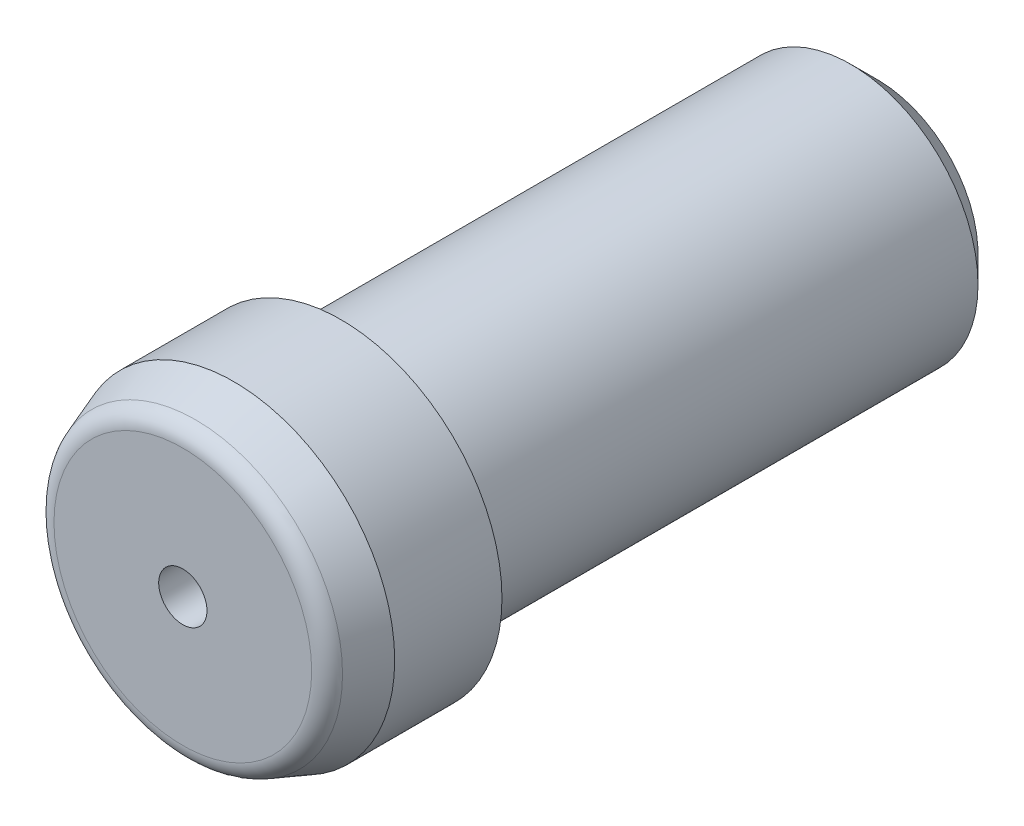
SolidWorks part; units mm, degrees
ref_plane "Front" through (0, 0, 0) normal (0, 0, 1) x (1, 0, 0)
ref_plane "Top" through (0, 0, 0) normal (0, 1, 0) x (1, 0, 0)
ref_plane "Right" through (0, 0, 0) normal (1, 0, 0) x (0, 0, -1)
sketch "Sketch1" plane through (0, 0, 0) normal (1, 0, 0) x (0, 0, -1)
  line L0 (0, 0) -> (0, 6.7417)
  line L1 (0, 6.7417) -> (2.413, 7.62)
  line L2 (2.413, 7.62) -> (7.493, 7.62)
  line L3 (7.493, 7.62) -> (7.493, 6.0325)
  line L4 (7.493, 6.0325) -> (32.893, 6.0325)
  line L5 (32.893, 6.0325) -> (32.893, 0)
  line L6 (32.893, 0) -> (0, 0)
  line L7 (0, 0) -> (-15.9922, 0) construction
  line L8 (0, 0) -> (0, -14.393) construction
  dimension "A" = 15.24
  dimension "D1" = 20
  dimension "D3" = 5.08
  dimension "D2" = 2.413
  dimension "D4" = 25.4
ref_axis "Axis1" through (0, 0, -133.35) along (0, 0, 1)
revolve "Revolve1" add sketch "Sketch1" angle 360 about axis through (0, 0, -133.35) along (0, 0, 1)
sketch "Sketch2" plane through (0, 0, 0) normal (1, 0, 0) x (0, 0, -1)
  line L0 (7.493, 7.62) -> (7.493, 6.0325) construction
  line L1 (7.239, 5.7785) -> (8.255, 5.7785) construction
  line L2 (7.239, 5.7785) -> (7.239, 6.7945) construction
  line L3 (7.239, 6.7945) -> (8.255, 6.7945) construction
  line L4 (8.255, 5.7785) -> (8.255, 6.7945) construction
  line L5 (7.493, 6.0325) -> (32.893, 6.0325) construction
  line L6 (7.2948, 6.3423) -> (7.747, 6.7945)
  line L7 (7.8028, 5.8343) -> (8.255, 6.2865)
  line L8 (7.239, 6.2076) -> (7.239, 5.969)
  line L9 (7.4295, 5.7785) -> (7.6681, 5.7785)
  line L10 (8.255, 6.2865) -> (8.255, 6.7945)
  line L11 (8.255, 6.7945) -> (7.747, 6.7945)
  arc A0 (7.2948, 6.3423) -> (7.239, 6.2076) centre (7.4295, 6.2076) ccw
  arc A1 (7.8028, 5.8343) -> (7.6681, 5.7785) centre (7.6681, 5.969) cw
  arc A2 (7.239, 5.969) -> (7.4295, 5.7785) centre (7.4295, 5.969) ccw
  point P14 (7.239, 6.2865)
  point P17 (7.747, 5.7785)
  dimension "D5" = 0.1905
  dimension "D1" = 0.254
  dimension "D2" = 0.254
  dimension "D3" = 1.016
  dimension "D4" = 1.016
revolve "Cut-Revolve1" cut sketch "Sketch2" angle 360 about axis through (0, 0, -133.35) along (0, 0, 1)
chamfer "Chamfer1" distance 1.27 angle 45 1 edges at (-6.0325, 0, -32.893)
fillet "Fillet1" radius 0.9144 1 edges at (-6.7417, 0, 0)
sketch "Sketch3" plane through (0, 0, 0) normal (0, 0, 1) x (1, 0, 0)
  circle A0 centre (0, 0) radius 1.143
  dimension "D1" = 2.286
extrude "Cut-Extrude1" cut sketch "Sketch3" against normal blind 2.54
sketch "Sketch4" plane through (0, 0, -32.893) normal (0, 0, -1) x (-1, 0, 0)
  circle A0 centre (0, 0) radius 1.143
  dimension "D1" = 2.286
extrude "Cut-Extrude2" cut sketch "Sketch4" against normal blind 2.54
equation "\"D1@Fillet1\" = \"A@Sketch1\"*.06"
